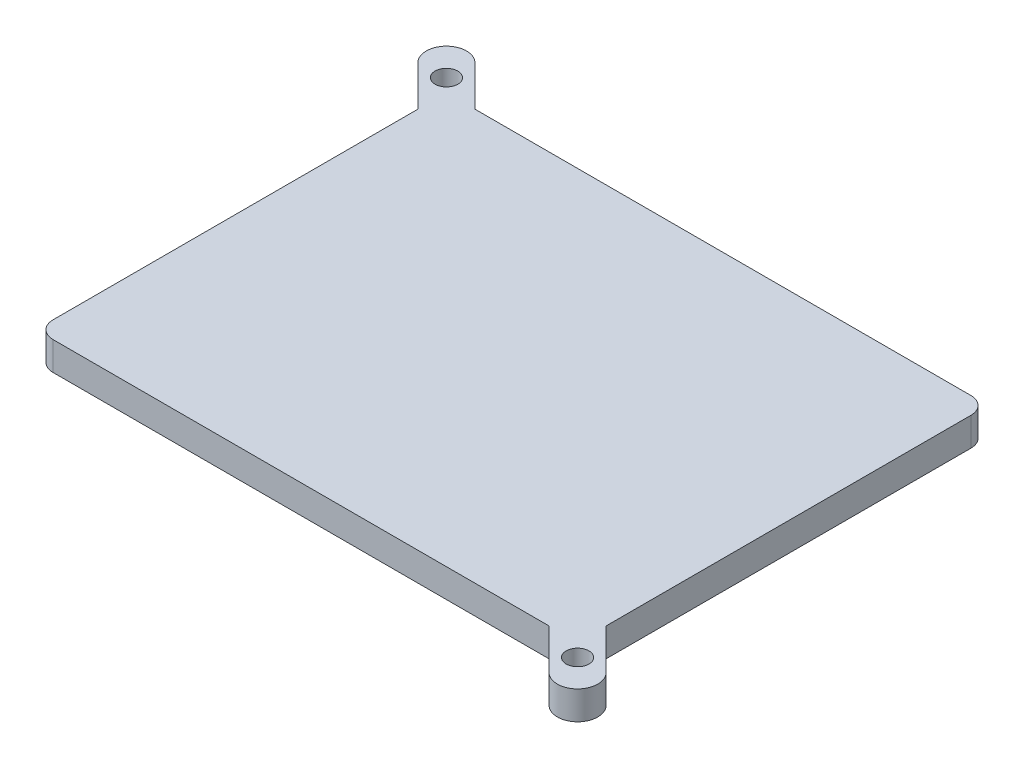
SolidWorks part; units mm, degrees
ref_plane "Plano frontal" through (0, 0, 0) normal (0, 0, 1) x (1, 0, 0)
ref_plane "Plano superior" through (0, 0, 0) normal (0, 1, 0) x (1, 0, 0)
ref_plane "Plano direito" through (0, 0, 0) normal (1, 0, 0) x (0, 0, -1)
sketch "Esboço1" plane through (0, 0, 0) normal (0, 1, 0) x (1, 0, 0)
  line L0 (9.0167, -15.2186) -> (9.0167, -20.2186) construction
  line L1 (-75.9833, 46.7814) -> (9.0167, 46.7814) construction
  line L2 (-75.9833, 46.7814) -> (-75.9833, -15.2186) construction
  line L3 (-75.9833, -15.2186) -> (9.0167, -15.2186) construction
  line L4 (9.0167, 46.7814) -> (9.0167, -15.2186) construction
  line L5 (-77.9833, 51.7814) -> (11.0167, 51.7814) construction
  line L6 (-80.9833, 48.7814) -> (-80.9833, -17.2186) construction
  line L7 (-77.9833, -20.2186) -> (11.0167, -20.2186) construction
  line L8 (14.0167, 48.7814) -> (14.0167, -17.2186) construction
  line L9 (9.0167, 46.7814) -> (9.0167, 51.7814) construction
  line L10 (-75.9833, -15.2186) -> (-80.9833, -15.2186) construction
  line L11 (9.0167, -15.2186) -> (14.0167, -15.2186) construction
  line L12 (9.0167, -20.2186) -> (16.0878, -27.2897)
  line L13 (16.0878, -27.2897) -> (21.0878, -22.2897) construction
  line L14 (21.0878, -22.2897) -> (14.0167, -15.2186)
  line L16 (9.0167, -20.2186) -> (14.0167, -15.2186) construction
  line L17 (21.0878, -27.2897) -> (11.5167, -17.7186) construction
  line L18 (-33.4833, 51.7814) -> (-33.4833, -20.2186) construction
  line L20 (14.0167, 15.7814) -> (-80.9833, 15.7814) construction
  line L21 (-77.9833, -20.2186) -> (9.0167, -20.2186)
  line L23 (14.0167, -15.2186) -> (14.0167, 48.7814)
  line L25 (-75.9833, 51.7814) -> (-80.9833, 46.7814)
  line L26 (-88.0543, 58.8524) -> (-78.4833, 49.2814) construction
  line L27 (-75.9833, 51.7814) -> (-83.0543, 58.8524)
  line L28 (-83.0543, 58.8524) -> (-88.0543, 53.8524) construction
  line L29 (-88.0543, 53.8524) -> (-80.9833, 46.7814)
  line L30 (11.0167, 51.7814) -> (-75.9833, 51.7814)
  line L31 (-80.9833, 46.7814) -> (-80.9833, -17.2186)
  arc A0 (-80.9833, -17.2186) -> (-77.9833, -20.2186) centre (-77.9833, -17.2186) ccw
  arc A1 (11.0167, -20.2186) -> (14.0167, -17.2186) centre (11.0167, -17.2186) ccw construction
  arc A2 (11.0167, 51.7814) -> (14.0167, 48.7814) centre (11.0167, 48.7814) cw
  arc A3 (-77.9833, 51.7814) -> (-80.9833, 48.7814) centre (-77.9833, 48.7814) ccw construction
  arc A4 (16.0878, -27.2897) -> (21.0878, -22.2897) centre (18.5878, -24.7897) ccw
  circle A5 centre (16.3023, -22.5042) radius 2
  arc A8 (-83.0543, 58.8524) -> (-88.0543, 53.8524) centre (-85.5543, 56.3524) ccw
  circle A9 centre (-83.2688, 54.0669) radius 2
  point P14 (-80.9833, -20.2186)
  point P17 (14.0167, -20.2186)
  point P20 (14.0167, 51.7814)
  dimension "D6" = 3
  dimension "D1" = 85
  dimension "D2" = 62
  dimension "D3" = 72
  dimension "D4" = 5
  dimension "D5" = 95
  dimension "D7" = 10
extrude "Ressalto-extrusão1" add sketch "Esboço1" along normal blind 5 contours L12 A4 L14 L23 A2 L30 L25 L31 A0 L21 A5 | L27 A8 L29 L25 A9
